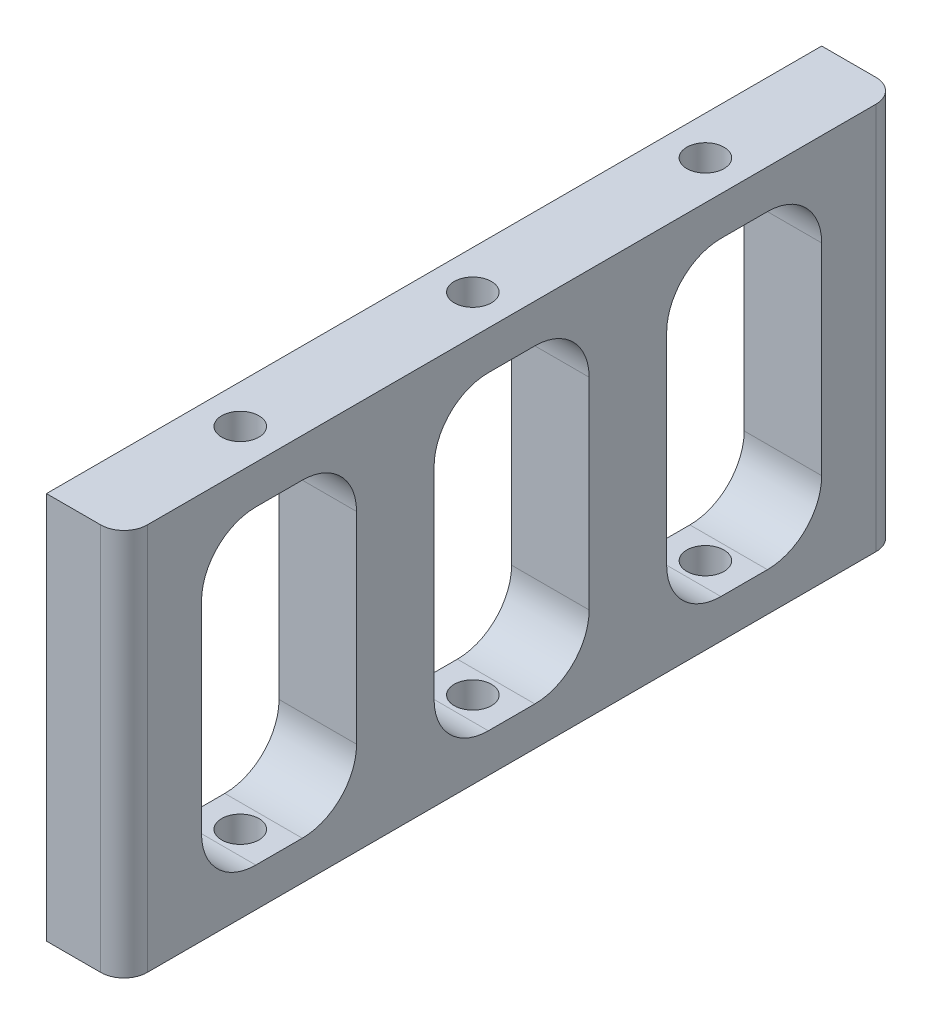
SolidWorks part; units mm, degrees
ref_plane "Plan de face" through (0, 0, 0) normal (0, 0, 1) x (1, 0, 0)
ref_plane "Plan de dessus" through (0, 0, 0) normal (0, 1, 0) x (1, 0, 0)
ref_plane "Plan de droite" through (0, 0, 0) normal (1, 0, 0) x (0, 0, -1)
sketch "Esquisse1" plane through (0, 0, 0) normal (1, 0, 0) x (0, 0, -1)
  line L0 (0, 0) -> (100, 0)
  line L1 (0, 0) -> (0, 50)
  line L2 (100, 0) -> (100, 50)
  line L3 (0, 50) -> (100, 50)
  line L4 (10, 45) -> (90, 45)
  line L5 (10, 45) -> (10, 5)
  line L6 (90, 45) -> (90, 5)
  line L7 (10, 5) -> (90, 5)
  line L8 (30, 45) -> (40, 45)
  line L9 (30, 45) -> (30, 5)
  line L10 (40, 45) -> (40, 5)
  line L11 (30, 5) -> (40, 5)
  line L12 (60, 45) -> (70, 45)
  line L13 (60, 45) -> (60, 5)
  line L14 (70, 45) -> (70, 5)
  line L15 (60, 5) -> (70, 5)
  line L16 (50, 50) -> (50, 0) construction
  line L17 (80, 50) -> (80, 0) construction
  line L19 (20, 50) -> (20, 0) construction
  dimension "D1" = 50
  dimension "D2" = 10
  dimension "D3" = 10
  dimension "D4" = 5
  dimension "D5" = 5
  dimension "D6" = 10
  dimension "D7" = 10
  dimension "D8" = 10
  dimension "D9" = 100
  dimension "D10" = 30
  dimension "D11" = 30
  dimension "D12" = 10
extrude "Boss.-Extru.1" add sketch "Esquisse1" along normal blind 10 contours L3 L1 L0 L2 L7 L5 L4 L6 | L14 L4 L13 L7 | L9 L11 L10 L4
sketch "Esquisse2" plane through (0, 0, 0) normal (0, -1, 0) x (1, 0, 0)
  line L1 (5, 0) -> (5, -100) construction
  line L2 (10, 0) -> (0, 0) construction
  line L3 (10, -100) -> (0, -100) construction
  line L5 (10, 0) -> (10, -100) construction
  line L6 (10, -50) -> (0, -50) construction
  line L7 (0, 0) -> (0, -100) construction
  circle A0 centre (5, -20) radius 2.4
  circle A1 centre (5, -50) radius 2.4
  circle A2 centre (5, -80) radius 2.4
  dimension "D1" = 4.8
  dimension "D2" = 4.8
  dimension "D3" = 4.8
  dimension "D4" = 30
  dimension "D5" = 30
extrude "Enlèv. mat.-Extru.1" cut sketch "Esquisse2" against normal through all
fillet "Congé1" radius 7 12 edges at (5, 45, -90) (5, 5, -90) (5, 5, -70) (5, 45, -70) (5, 45, -60) (5, 45, -40) (5, 5, -60) (5, 5, -10) (5, 45, -10) (5, 45, -30) (5, 5, -40) (5, 5, -30)
fillet "Congé2" radius 3 2 edges at (10, 25, -100) (10, 25, 0)
